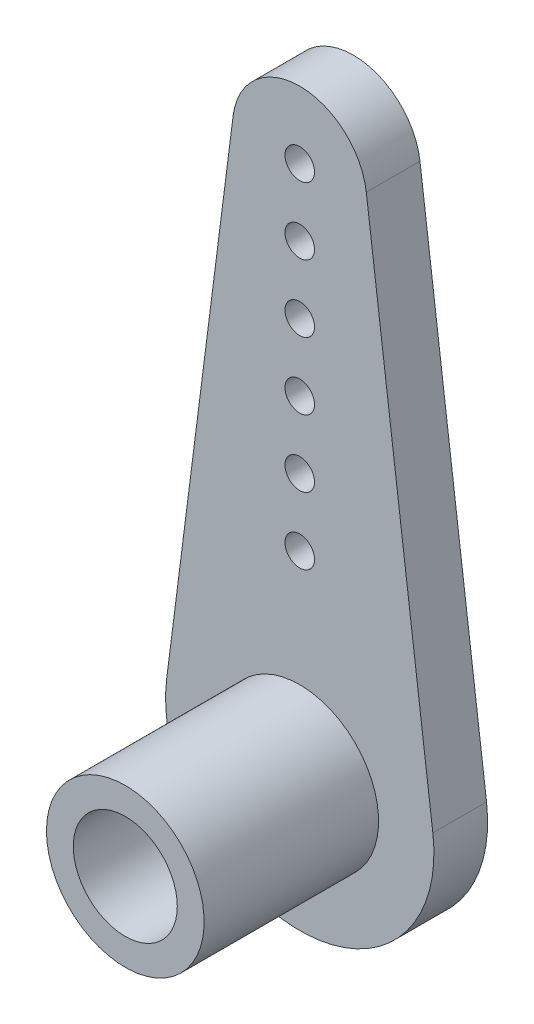
SolidWorks part; units mm, degrees
material "PLA"
ref_plane "Front Plane" through (0, 0, 0) normal (0, 0, 1) x (1, 0, 0)
ref_plane "Top Plane" through (0, 0, 0) normal (0, 1, 0) x (1, 0, 0)
ref_plane "Right Plane" through (0, 0, 0) normal (1, 0, 0) x (0, 0, -1)
sketch "Sketch1" plane through (0, 0, 0) normal (0, 0, 1) x (1, 0, 0)
  line L0 (-4.9598, 40.1329) -> (-9.9196, 1.2658)
  line L1 (0, -55) -> (0, 55) construction
  line L2 (4.9598, 40.1329) -> (9.9196, 1.2658)
  arc A0 (-9.9196, 1.2658) -> (9.9196, 1.2658) centre (0, 0) ccw
  arc A1 (4.9598, 40.1329) -> (-4.9598, 40.1329) centre (0, 39.5) ccw
  arc A2 (9.9196, 1.2658) -> (-9.9196, 1.2658) centre (0, 0) ccw construction
  arc A3 (-4.9598, 40.1329) -> (4.9598, 40.1329) centre (0, 39.5) ccw construction
  circle A4 centre (0, 39.5) radius 1.1
  circle A5 centre (0, 34.5) radius 1.1
  circle A6 centre (0, 29.5) radius 1.1
  circle A7 centre (0, 24.5) radius 1.1
  circle A8 centre (0, 19.5) radius 1.1
  circle A9 centre (0, 14.5) radius 1.1
  dimension "D1" = 39.5
  dimension "D2" = 20
  dimension "D3" = 10
  dimension "D4" = 2.2
  dimension "D5" = 6
extrude "Boss-Extrude1" add sketch "Sketch1" along normal blind 4
sketch "Sketch2" plane through (0, 0, 4) normal (0, 0, 1) x (1, 0, 0)
  circle A0 centre (0, 0) radius 5.875
  dimension "D1" = 11.75
extrude "Boss-Extrude2" add sketch "Sketch2" along normal blind 13
sketch "Sketch3" plane through (0, 0, 0) normal (0, 0, 1) x (1, 0, 0)
  circle A0 centre (0, 0) radius 3.875
  circle A1 centre (0, 0) radius 5.875 construction
  dimension "D1" = 2
extrude "Cut-Extrude1" cut sketch "Sketch3" along normal through all both and the other way through all
